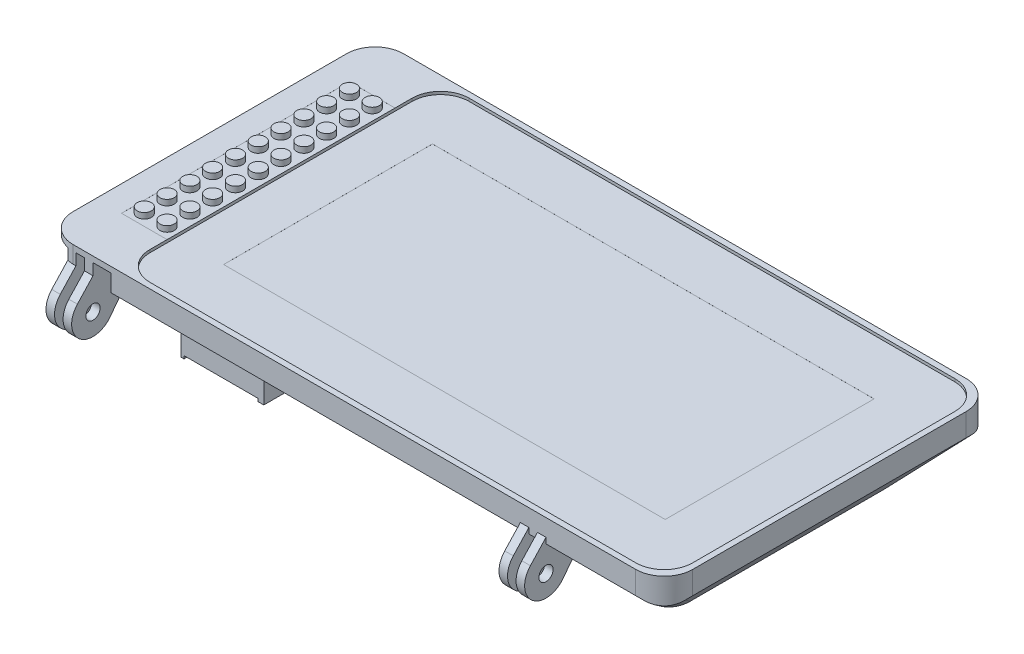
SolidWorks part; units mm, degrees
material "ABS"
ref_plane "Alzado" through (0, 0, 0) normal (0, 0, 1) x (1, 0, 0)
ref_plane "Planta" through (0, 0, 0) normal (0, 1, 0) x (1, 0, 0)
ref_plane "Vista lateral" through (0, 0, 0) normal (1, 0, 0) x (0, 0, -1)
sketch "Croquis1" plane through (0, 0, 0) normal (0, 1, 0) x (1, 0, 0)
  line L0 (-55, 0) -> (55, 0) construction
  line L1 (-108.75, -58) -> (108.75, -58)
  line L2 (-108.75, -58) -> (-108.75, 58)
  line L3 (-108.75, 58) -> (108.75, 58)
  line L4 (108.75, -58) -> (108.75, 58)
  line L5 (-108.75, -58) -> (108.75, 58) construction
  line L6 (-108.75, 58) -> (108.75, -58) construction
  line L7 (-83.75, -56) -> (106.75, -56)
  line L8 (-83.75, -56) -> (-83.75, 56)
  line L9 (-83.75, 56) -> (106.75, 56)
  line L10 (106.75, -56) -> (106.75, 56)
  line L11 (-83.75, -56) -> (106.75, 56) construction
  line L12 (-83.75, 56) -> (106.75, -56) construction
  line L13 (-91.75, 40) -> (-91.75, -40) construction
  line L14 (-99.75, -40) -> (-83.75, -40)
  line L15 (-99.75, -40) -> (-99.75, 40)
  line L16 (-99.75, 40) -> (-83.75, 40)
  line L17 (-83.75, -40) -> (-83.75, 40)
  line L18 (-99.75, -40) -> (-83.75, 40) construction
  line L19 (-99.75, 40) -> (-83.75, -40) construction
  line L20 (-67.25, -36.6556) -> (87.75, -36.6556)
  line L21 (-67.25, -36.6556) -> (-67.25, 36.6556)
  line L22 (-67.25, 36.6556) -> (87.75, 36.6556)
  line L23 (87.75, -36.6556) -> (87.75, 36.6556)
  line L24 (-67.25, -36.6556) -> (87.75, 36.6556) construction
  line L25 (-67.25, 36.6556) -> (87.75, -36.6556) construction
  circle A0 centre (-95.75, 36) radius 2.5
  circle A1 centre (-87.75, 36) radius 2.5
  circle A2 centre (-95.75, 28) radius 2.5
  circle A3 centre (-87.75, 28) radius 2.5
  circle A4 centre (-95.75, 20) radius 2.5
  circle A5 centre (-87.75, 20) radius 2.5
  circle A6 centre (-95.75, 12) radius 2.5
  circle A7 centre (-87.75, 12) radius 2.5
  circle A8 centre (-95.75, 4) radius 2.5
  circle A9 centre (-87.75, 4) radius 2.5
  circle A10 centre (-95.75, -4) radius 2.5
  circle A11 centre (-87.75, -4) radius 2.5
  circle A12 centre (-95.75, -12) radius 2.5
  circle A13 centre (-87.75, -12) radius 2.5
  circle A14 centre (-95.75, -20) radius 2.5
  circle A15 centre (-87.75, -20) radius 2.5
  circle A16 centre (-95.75, -28) radius 2.5
  circle A17 centre (-87.75, -28) radius 2.5
  circle A18 centre (-95.75, -36) radius 2.5
  circle A19 centre (-87.75, -36) radius 2.5
  point P0 (0, 0)
  point P6 (11.5, 0)
  point P13 (-91.75, 0)
  point P18 (10.25, 0)
  dimension "D9" = 5
  dimension "D10" = 4
  dimension "D12" = 4
  dimension "D1" = 116
  dimension "D2" = 217.5
  dimension "D3" = 2
  dimension "D4" = 2
  dimension "D5" = 25
  dimension "D6" = 16
  dimension "D7" = 19
  dimension "D8" = 155
  dimension "D11" = 8
  dimension "D14" = 80
  dimension "D13" = 10
sketch "Croquis2" plane through (0, 0, 0) normal (0, 1, 0) x (1, 0, 0)
  line L1 (-108.75, -58) -> (108.75, -58)
  line L2 (-108.75, -58) -> (-108.75, 58)
  line L3 (-108.75, 58) -> (108.75, 58)
  line L4 (108.75, -58) -> (108.75, 58)
  line L5 (-108.75, -58) -> (108.75, 58) construction
  line L6 (-108.75, 58) -> (108.75, -58) construction
  point P0 (0, 0)
extrude "Saliente-Extruir1" add sketch "Croquis2" along normal mid plane 24
sketch "Croquis3" plane through (0, 12, 0) normal (0, 1, 0) x (1, 0, 0)
  line L6 (-73.75, 56) -> (96.75, 56)
  line L8 (-83.75, 46) -> (-83.75, -46)
  line L9 (-73.75, -56) -> (96.75, -56)
  line L10 (106.75, 46) -> (106.75, -46)
  arc A0 (96.75, 56) -> (106.75, 46) centre (96.75, 46) cw
  arc A1 (96.75, -56) -> (106.75, -46) centre (96.75, -46) ccw
  arc A2 (-83.75, -46) -> (-73.75, -56) centre (-73.75, -46) ccw
  arc A3 (-83.75, 46) -> (-73.75, 56) centre (-73.75, 46) cw
  point P9 (106.75, -56)
  point P16 (-83.75, 56)
  dimension "D1" = 10
extrude "Cortar-Extruir1" cut sketch "Croquis3" against normal blind 1
sketch "Croquis4" plane through (0, 12, 0) normal (0, 1, 0) x (1, 0, 0)
  line L1 (-99.75, 40) -> (-83.75, 40)
  line L2 (-99.75, 40) -> (-99.75, -40)
  line L3 (-99.75, -40) -> (-83.75, -40)
  line L4 (-83.75, 40) -> (-83.75, -40)
extrude "Cortar-Extruir2" cut sketch "Croquis4" against normal blind 0.01
sketch "Croquis5" plane through (0, 11.99, 0) normal (0, 1, 0) x (1, 0, 0)
  circle A0 centre (-95.75, 36) radius 2.5
  circle A1 centre (-87.75, 36) radius 2.5
  circle A2 centre (-87.75, 28) radius 2.5
  circle A3 centre (-95.75, 28) radius 2.5
  circle A4 centre (-87.75, 20) radius 2.5
  circle A5 centre (-95.75, 20) radius 2.5
  circle A6 centre (-87.75, 12) radius 2.5
  circle A7 centre (-95.75, 12) radius 2.5
  circle A8 centre (-87.75, 4) radius 2.5
  circle A9 centre (-95.75, 4) radius 2.5
  circle A10 centre (-87.75, -4) radius 2.5
  circle A11 centre (-95.75, -4) radius 2.5
  circle A12 centre (-87.75, -12) radius 2.5
  circle A13 centre (-95.75, -12) radius 2.5
  circle A14 centre (-87.75, -20) radius 2.5
  circle A15 centre (-95.75, -20) radius 2.5
  circle A16 centre (-87.75, -28) radius 2.5
  circle A17 centre (-95.75, -28) radius 2.5
  circle A18 centre (-87.75, -36) radius 2.5
  circle A19 centre (-95.75, -36) radius 2.5
  dimension "D1" = 10
extrude "Saliente-Extruir2" add sketch "Croquis5" along normal blind 2
sketch "Croquis6" plane through (0, 11, 0) normal (0, 1, 0) x (1, 0, 0)
  line L1 (-67.25, 36.6556) -> (87.75, 36.6556)
  line L2 (-67.25, 36.6556) -> (-67.25, -36.6556)
  line L3 (-67.25, -36.6556) -> (87.75, -36.6556)
  line L4 (87.75, 36.6556) -> (87.75, -36.6556)
extrude "Cortar-Extruir3" cut sketch "Croquis6" against normal blind 0.01
sketch "Croquis7" plane through (0, -12, 0) normal (0, -1, 0) x (1, 0, 0)
  line L0 (94, 58) -> (94, -58) construction
  line L1 (94, 41.5) -> (-94, 41.5)
  line L2 (94, 41.5) -> (94, -41.5)
  line L3 (94, -41.5) -> (-94, -41.5)
  line L4 (-94, 41.5) -> (-94, -41.5)
  line L5 (94, 41.5) -> (-94, -41.5) construction
  line L6 (94, -41.5) -> (-94, 41.5) construction
  line L7 (-108.75, 58) -> (108.75, 58) construction
  line L8 (108.75, -58) -> (-108.75, -58) construction
  point P0 (0, 0)
  dimension "D1" = 83
  dimension "D2" = 188
ref_plane "Plano1" through (0, 4, 0) normal (0, 1, 0) x (1, 0, 0)
sketch "Croquis12" plane through (0, 4, 0) normal (0, 1, 0) x (1, 0, 0)
  line L1 (-108.75, 58) -> (108.75, 58)
  line L2 (-108.75, 58) -> (-108.75, -58)
  line L3 (-108.75, -58) -> (108.75, -58)
  line L4 (108.75, 58) -> (108.75, -58)
ref_plane "Plano2" through (-31.6273, 0, 28.2729) normal (-0.7455, 0, 0.6665) x (0.6665, 0, 0.7455)
sketch "Croquis13" plane through (-31.6273, 0, 28.2729) normal (-0.7455, 0, 0.6665) x (0.6665, 0, 0.7455)
  line L0 (-93.5874, -12) -> (-115.7192, 4)
  line L1 (-115.7192, 4) -> (-115.7192, -12)
  line L2 (-115.7192, -12) -> (-93.5874, -12)
sweep "Cortar-Barrer2" cut profiles "Croquis13" path "Croquis7"
sketch "Croquis14" plane through (0, 0, 0) normal (0, 0, 1) x (1, 0, 0)
  line L0 (-94, -12) -> (-108.75, -12)
  line L1 (-108.75, -12) -> (-108.75, 4)
  line L2 (-108.75, 4) -> (-94, -12)
  line L3 (94, -12) -> (108.75, 4)
  line L4 (108.75, 4) -> (108.75, -12)
  line L5 (108.75, -12) -> (94, -12)
extrude "Cortar-Extruir5" cut sketch "Croquis14" against normal through all both and the other way through all
sketch "Croquis15" plane through (0, -12, 0) normal (0, -1, 0) x (1, 0, 0)
  line L0 (-94, -41.5) -> (94, -41.5) construction
  line L1 (-16.5, -53.5) -> (-49, -53.5)
  line L2 (-16.5, -53.5) -> (-16.5, -37.5)
  line L3 (-16.5, -37.5) -> (-49, -37.5)
  line L4 (-49, -53.5) -> (-49, -37.5)
  line L5 (-94, 41.5) -> (-94, -41.5) construction
  dimension "D1" = 32.5
  dimension "D2" = 16
  dimension "D3" = 4
  dimension "D4" = 45
extrude "Cortar-Extruir6" cut sketch "Croquis15" against normal blind 10.5
sketch "Croquis16" plane through (0, -1.5, 0) normal (0, -1, 0) x (1, 0, 0)
  line L0 (-16.5, -52.3281) -> (-16.5, -41.5) construction
  line L1 (-49, -37.5) -> (-16.5, -37.5)
  line L2 (-49, -37.5) -> (-49, -53.5)
  line L3 (-49, -53.5) -> (-16.5, -53.5)
  line L4 (-16.5, -37.5) -> (-16.5, -53.5)
  dimension "D1" = 16
extrude "Saliente-Extruir4" add sketch "Croquis16" along normal blind 2 and the other way blind 2
sketch "Croquis17" plane through (0, -3.5, 0) normal (0, -1, 0) x (1, 0, 0)
  line L0 (-49, -52) -> (-50.5, -52)
  line L1 (-50.5, -52) -> (-50.5, -55.5)
  line L2 (-50.5, -55.5) -> (-15, -55.5)
  line L3 (-15, -55.5) -> (-15, -52)
  line L4 (-15, -52) -> (-16.5, -52)
  line L5 (-16.5, -52) -> (-16.5, -53.5)
  line L6 (-16.5, -53.5) -> (-49, -53.5)
  line L7 (-49, -50.2656) -> (-49, -53.5) construction
  line L8 (-49, -53.5) -> (-49, -52)
  dimension "D1" = 1.5
  dimension "D2" = 1.5
  dimension "D3" = 2
  dimension "D4" = 3.5
  dimension "D5" = 3.5
extrude "Saliente-Extruir10" add sketch "Croquis17" against normal blind 5 from offset 2 offset against normal yes
sketch "Croquis18" plane through (0, -12, 0) normal (0, -1, 0) x (1, 0, 0)
  line L0 (-16.5, -41.5) -> (94, -41.5) construction
  line L1 (-16.5, -41.5) -> (-16.5, -37.5) construction
  line L2 (-94, 0) -> (93.4097, 0) construction
  line L3 (-94, 41.5) -> (-94, -41.5) construction
  line L4 (14.5695, 0) -> (-14.5695, 0) construction
  circle A0 centre (-11.5, -37.5) radius 2.5
  circle A1 centre (63.5, -37.5) radius 2.5
  circle A2 centre (63.5, 37.5) radius 2.5
  circle A3 centre (-11.5, 37.5) radius 2.5
  dimension "D1" = 5
  dimension "D2" = 4
  dimension "D4" = 75
  dimension "D3" = 5
extrude "Cortar-Extruir7" cut sketch "Croquis18" against normal blind 9
sketch "Croquis19" plane through (0, -12, 0) normal (0, -1, 0) x (1, 0, 0)
  line L0 (-16.5, -41.5) -> (94, -41.5) construction
  line L1 (94, -41.5) -> (94, 41.5) construction
  line L2 (14.5695, 0) -> (-14.5695, 0) construction
  circle A0 centre (73.5, -35) radius 3.5
  circle A1 centre (73.5, 35) radius 3.5
  dimension "D1" = 7
  dimension "D2" = 6.5
  dimension "D3" = 20.5
extrude "Cortar-Extruir8" cut sketch "Croquis19" against normal blind 4
sketch "Croquis20" plane through (0, -8, 0) normal (0, -1, 0) x (1, 0, 0)
  circle A0 centre (73.5, 35) radius 1.5
  circle A1 centre (73.5, -35) radius 1.5
  dimension "D1" = 3
  dimension "D2" = 3
extrude "Cortar-Extruir9" cut sketch "Croquis20" against normal blind 4
sketch "Croquis21" plane through (0, -12, 0) normal (0, -1, 0) x (1, 0, 0)
  line L0 (-22.5, -34) -> (-22.5, -12.7)
  line L1 (-22.5, -12.7) -> (-10.5, -12.7)
  line L2 (-10.5, -12.7) -> (-10.5, 13.3)
  line L3 (-10.5, 13.3) -> (-22.5, 13.3)
  line L4 (-22.5, 13.3) -> (-22.5, 30.3)
  line L5 (-22.5, 30.3) -> (-18.5, 30.3)
  line L6 (-18.5, 30.3) -> (-18.5, 41.5)
  line L7 (94, 41.5) -> (-94, 41.5) construction
  line L8 (-22.5, -34) -> (-30.5, -34)
  line L9 (-30.5, -34) -> (-30.5, -31.5)
  line L10 (-30.5, -31.5) -> (-49.5, -31.5)
  line L11 (-49.5, -31.5) -> (-49.5, -35.5)
  line L13 (-56.5, -35.5) -> (-56.5, -31.5)
  line L14 (-56.5, -31.5) -> (-86, -31.5)
  line L15 (-86, -31.5) -> (-86, -34)
  line L16 (-86, -34) -> (-93, -34)
  line L17 (-93, -34) -> (-93, -31.5)
  line L18 (-93, -31.5) -> (-94, -31.5)
  line L19 (-94, 41.5) -> (-94, -41.5) construction
  line L20 (-16.5, -37.5) -> (-49, -37.5) construction
  line L21 (-16.5, -50.2656) -> (-16.5, -37.5) construction
  line L23 (-18.5, 41.5) -> (-18.5, 56.8)
  line L24 (-18.5, 56.8) -> (-40.5, 56.8)
  line L25 (-40.5, 56.8) -> (-40.5, 30.3)
  line L26 (-40.5, 30.3) -> (-37.5, 30.3)
  line L27 (-37.5, 30.3) -> (-37.5, 28.8)
  line L28 (-37.5, 28.8) -> (-45.5, 28.8)
  line L29 (-45.5, 28.8) -> (-45.5, 34.8)
  line L31 (-52.5, 34.8) -> (-52.5, 29.8)
  line L32 (-52.5, 29.8) -> (-62.5, 29.8)
  line L33 (-62.5, 29.8) -> (-62.5, 28.8)
  line L34 (-62.5, 28.8) -> (-71.5, 28.8)
  line L35 (-71.5, 28.8) -> (-71.5, 30.3)
  line L36 (-71.5, 30.3) -> (-68.5, 30.3)
  line L37 (-68.5, 30.3) -> (-68.5, 56.8)
  line L38 (-68.5, 56.8) -> (-85.5, 56.8)
  line L39 (-85.5, 56.8) -> (-85.5, 44.8)
  line L40 (-85.5, 44.8) -> (-83.5, 44.8)
  line L41 (-83.5, 44.8) -> (-83.5, 30.3)
  line L42 (-83.5, 30.3) -> (-79.5, 30.3)
  line L43 (-79.5, 30.3) -> (-79.5, 28.8)
  line L44 (-79.5, 28.8) -> (-108.75, 28.8)
  line L45 (-108.75, -58) -> (-108.75, 58) construction
  line L46 (-108.75, 28.8) -> (-108.75, -31.5)
  line L47 (-108.75, -31.5) -> (-94, -31.5)
  line L48 (-52.5, 34.8) -> (-45.5, 34.8) construction
  arc A0 (-56.5, -35.5) -> (-49.5, -35.5) centre (-53, -35.5) ccw
  arc A1 (-45.5, 34.8) -> (-52.5, 34.8) centre (-49, 34.8) ccw
  dimension "D12" = 3.5
  dimension "D22" = 3.5
  dimension "D1" = 3.5
  dimension "D2" = 26
  dimension "D3" = 12
  dimension "D4" = 21.3
  dimension "D5" = 6
  dimension "D6" = 17
  dimension "D7" = 4
  dimension "D8" = 8
  dimension "D9" = 19
  dimension "D10" = 6
  dimension "D11" = 7
  dimension "D13" = 4
  dimension "D14" = 7
  dimension "D15" = 1
  dimension "D16" = 26.5
  dimension "D17" = 22
  dimension "D18" = 3
  dimension "D19" = 1.5
  dimension "D20" = 8
  dimension "D21" = 7
  dimension "D23" = 6
  dimension "D24" = 1
  dimension "D25" = 9
  dimension "D26" = 10
  dimension "D27" = 1.5
  dimension "D28" = 3
  dimension "D29" = 17
  dimension "D30" = 12
  dimension "D32" = 2
  dimension "D33" = 8
  dimension "D34" = 1.5
extrude "Cortar-Extruir10" cut sketch "Croquis21" against normal blind 13.5
sketch "Croquis22" plane through (0, 1.5, 0) normal (0, -1, 0) x (1, 0, 0)
  line L0 (-37.5, 28.8) -> (-45.5, 28.8) construction
  line L1 (-22.5, 30.3) -> (-27.5, 30.3)
  line L2 (-22.5, 30.3) -> (-22.5, 28.8)
  line L3 (-22.5, 28.8) -> (-27.5, 28.8)
  line L4 (-27.5, 30.3) -> (-27.5, 28.8)
  dimension "D1" = 1.5
  dimension "D2" = 5
extrude "Saliente-Extruir11" add sketch "Croquis22" along normal blind 11
sketch "Croquis23" plane through (0, -12, 0) normal (0, -1, 0) x (1, 0, 0)
  line L0 (-68.5, 30.3) -> (-68.5, 41.5) construction
  line L2 (-42.5, 50.3) -> (-42.5, 31.3059)
  line L3 (-41.5059, 30.3059) -> (-40.5, 30.3)
  line L4 (-40.5, 30.3) -> (-37.5, 30.3)
  line L5 (-37.5, 30.3) -> (-37.5, 28.8)
  line L6 (-37.5, 28.8) -> (-45.5, 28.8)
  line L7 (-45.5, 28.8) -> (-45.5, 34.8)
  line L8 (-42.5, 50.3) -> (-66.5, 50.3)
  line L9 (-66.5, 50.3) -> (-66.5, 31.3)
  line L10 (-67.5, 30.3) -> (-71.5, 30.3)
  line L11 (-71.5, 30.3) -> (-71.5, 28.8)
  line L12 (-71.5, 28.8) -> (-45.5, 28.8)
  line L13 (-40.5, 41.5) -> (-40.5, 30.3) construction
  arc A0 (-42.5, 31.3059) -> (-41.5059, 30.3059) centre (-41.5, 31.3059) ccw
  arc A1 (-66.5, 31.3) -> (-67.5, 30.3) centre (-67.5, 31.3) cw
  line M2 (-68.5, 30.3) -> (-71.5, 30.3)
  line M3 (-71.5, 30.3) -> (-71.5, 28.8)
  line M4 (-71.5, 28.8) -> (-62.5, 28.8)
  line M5 (-62.5, 28.8) -> (-62.5, 29.8)
  line M6 (-62.5, 29.8) -> (-52.5, 29.8)
  line M7 (-52.5, 29.8) -> (-52.5, 34.8)
  arc M8 (-52.5, 34.8) -> (-45.5, 34.8) centre (-49, 34.8) cw
  line M9 (-45.5, 34.8) -> (-45.5, 28.8)
  line M10 (-45.5, 28.8) -> (-37.5, 28.8)
  line M11 (-37.5, 28.8) -> (-37.5, 30.3)
  line M12 (-37.5, 30.3) -> (-40.5, 30.3)
  line M14 (-40.5, 41.5) -> (-68.5, 41.5)
  dimension "D1" = 1
  dimension "D2" = 21.5
  dimension "D3" = 2
  dimension "D4" = 2
sketch "Croquis24" plane through (0, 1.5, 0) normal (0, -1, 0) x (1, 0, 0)
  line L0 (-52.5, 29.8) -> (-45.5, 29.8)
  line L1 (-45.5, 28.8) -> (-45.5, 34.8) construction
  line L2 (-45.5, 29.8) -> (-45.5, 34.8)
  line L3 (-52.5, 34.8) -> (-52.5, 29.8)
  arc A0 (-45.5, 34.8) -> (-52.5, 34.8) centre (-49, 34.8) ccw
extrude "Saliente-Extruir12" add sketch "Croquis24" along normal blind 6
extrude "Cortar-Extruir12" cut sketch "Croquis23" against normal blind 1 contours L8 L9 L2 M14 | L9 A1 L10 L3 A0 L2 M2 M3 M4 M5 M6 M7 M8 M9 M10 M11 M12 M14
sketch "Croquis25" plane through (0, -11, 0) normal (0, -1, 0) x (1, 0, 0)
  line L0 (-42.5, 41.5) -> (-42.5, 31.3059) construction
  line L1 (-42.5, 38.8) -> (-71.5, 38.8)
  line L2 (-42.5, 38.8) -> (-42.5, 47.3)
  line L3 (-42.5, 47.3) -> (-71.5, 47.3)
  line L4 (-71.5, 38.8) -> (-71.5, 47.3)
  line L5 (-62.5, 29.8) -> (-52.5, 29.8) construction
  dimension "D1" = 9
  dimension "D2" = 8.5
extrude "Cortar-Extruir13" cut sketch "Croquis25" against normal blind 11
sketch "Croquis26" plane through (0, 0, 0) normal (0, -1, 0) x (1, 0, 0)
  line L1 (-69.5, 47.3) -> (-42.5, 47.3)
  line L2 (-69.5, 47.3) -> (-69.5, 49.3)
  line L3 (-69.5, 49.3) -> (-42.5, 49.3)
  line L4 (-42.5, 47.3) -> (-42.5, 49.3)
  dimension "D1" = 2
extrude "Saliente-Extruir13" add sketch "Croquis26" along normal blind 11
sketch "Croquis27" plane through (0, -12, 0) normal (0, -1, 0) x (1, 0, 0)
  line L1 (-69.5, 49.3) -> (-68.5, 49.3)
  line L2 (-69.5, 49.3) -> (-69.5, 31.3)
  line L3 (-70.5, 30.3) -> (-68.5, 30.3)
  line L4 (-68.5, 49.3) -> (-68.5, 30.3)
  line L5 (-42.5, 49.3) -> (-40.5, 49.3)
  line L6 (-42.5, 49.3) -> (-42.5, 31.3)
  line L7 (-41.5, 30.3) -> (-40.5, 30.3)
  line L8 (-40.5, 49.3) -> (-40.5, 30.3)
  arc A0 (-42.5, 31.3) -> (-41.5, 30.3) centre (-41.5, 31.3) ccw
  arc A1 (-69.5, 31.3) -> (-70.5, 30.3) centre (-70.5, 31.3) cw
  dimension "D1" = 1
extrude "Saliente-Extruir14" add sketch "Croquis27" against normal blind 14
sketch "Croquis28" plane through (0, 4, 0) normal (0, 1, 0) x (1, 0, 0)
  line L0 (-108.75, 58) -> (-85.75, 58)
  line L1 (-108.75, 58) -> (108.75, 58) construction
  line L2 (-85.75, 58) -> (-85.75, 43)
  line L3 (-85.75, 43) -> (-102.75, 43)
  line L4 (-102.75, 43) -> (-102.75, 33)
  line L5 (-102.75, 33) -> (-108.75, 33)
  line L6 (-108.75, 58) -> (-108.75, -58) construction
  line L7 (-108.75, 33) -> (-108.75, 58)
  dimension "D1" = 25
  dimension "D2" = 6
  dimension "D3" = 10
  dimension "D4" = 23
extrude "Cortar-Extruir14" cut sketch "Croquis28" against normal blind 23
sketch "Croquis29" plane through (0, 4, 0) normal (0, 1, 0) x (1, 0, 0)
  line L0 (-108.75, -29.5) -> (-102.75, -29.5)
  line L1 (-108.75, 33) -> (-108.75, -58) construction
  line L2 (-102.75, -29.5) -> (-102.75, -44.8)
  line L3 (-102.75, -44.8) -> (-85.5, -44.8)
  line L4 (-85.5, -44.8) -> (-85.5, -58)
  line L5 (108.75, -58) -> (-108.75, -58) construction
  line L6 (-85.5, -58) -> (-108.75, -58)
  line L7 (-108.75, -58) -> (-108.75, -29.5)
  dimension "D1" = 28.5
  dimension "D2" = 6
extrude "Cortar-Extruir15" cut sketch "Croquis29" against normal blind 23 and the other way blind 6
sketch "Croquis30" plane through (0, -12, 0) normal (0, -1, 0) x (1, 0, 0)
  line L0 (108.75, 58) -> (-85.5, 58) construction
  line L1 (22.5, 26.5) -> (48.5, 26.5)
  line L2 (22.5, 26.5) -> (22.5, 58)
  line L3 (22.5, 58) -> (48.5, 58)
  line L4 (48.5, 26.5) -> (48.5, 58)
  line L5 (-18.5, 41.5) -> (-18.5, 55.4219) construction
  line L6 (94, 41.5) -> (-18.5, 41.5) construction
  dimension "D1" = 26
  dimension "D2" = 41
  dimension "D3" = 15
extrude "Cortar-Extruir16" cut sketch "Croquis30" against normal blind 16
sketch "Croquis31" plane through (0, 4, 0) normal (0, -1, 0) x (1, 0, 0)
  line L0 (-94, -31.5) -> (-107.75, -31.5)
  line L1 (-106.4453, -31.5) -> (-93, -31.5) construction
  line L2 (-107.75, -31.5) -> (-107.75, 28.8)
  line L3 (-79.5, 28.8) -> (-106.4453, 28.8) construction
  line L4 (-107.75, 28.8) -> (-94, 28.8)
  line L5 (-94, 28.8) -> (-94, 30.3)
  line L6 (-94, 30.3) -> (-108.75, 30.3)
  line L7 (-108.75, 29.5) -> (-108.75, 58) construction
  line L8 (-108.75, 30.3) -> (-108.75, -33)
  line L9 (-108.75, -33) -> (-94, -33)
  line L10 (-94, -31.5) -> (-94, -41.5) construction
  line L11 (-94, -33) -> (-94, -31.5)
  dimension "D1" = 1.5
  dimension "D2" = 1
extrude "Saliente-Extruir15" add sketch "Croquis31" along normal blind 12 and the other way blind 6
fillet "Redondeo1" radius 4 4 edges at (-108.75, 1, 30.3) (-108.75, -2, -33) (-107.75, -2.5424, -31.5) (-107.75, -2.5424, 28.8)
sketch "Croquis32" plane through (0, 0, 44.8) normal (0, 0, 1) x (1, 0, 0)
  line L0 (-102.75, 5) -> (-96.95, -8.8)
  line L1 (-102.75, 10) -> (-102.75, -2.5085) construction
  line L2 (-96.95, -8.8) -> (-102.75, -2.5085)
  line L3 (-102.75, -2.5085) -> (-102.75, 5)
  line L4 (-85.5, 10) -> (-102.75, 10) construction
  dimension "D1" = 5
extrude "Cortar-Extruir17" cut sketch "Croquis32" against normal up to surface (14.5 mm away) up to face at (-102.5375, 0.2983, 30.3)
ref_plane "Plano3" through (-100.75, 0, 0) normal (-1, 0, 0) x (0, 0, 1)
sketch "Croquis33" plane through (-100.75, 0, 0) normal (-1, 0, 0) x (0, 0, 1)
  line L0 (58, 10) -> (58, 6)
  line L1 (58, 10) -> (44.8, 10)
  line L2 (44.8, 10) -> (44.8, 0)
  line L3 (44.8, -8.8) -> (44.8, 5) construction
  line L4 (44.8, 0) -> (52.0227, -9.5301)
  line L5 (58, 6) -> (63.4864, 0.1136)
  line L7 (58, 10) -> (58, -5) construction
  arc A0 (52.0227, -9.5301) -> (63.4864, 0.1136) centre (58, -5) ccw
  circle A1 centre (58, -5) radius 2.5
  dimension "D3" = 15
  dimension "D5" = 5
  dimension "D1" = 10
  dimension "D2" = 15
  dimension "D4" = 6
extrude "Saliente-Extruir16" add sketch "Croquis33" against normal blind 3
pattern_linear "MatrizL1" count 2 spacing 6 along (1, 0, 0) of "Saliente-Extruir16"
sketch "Croquis34" plane through (48.5, 0, 0) normal (-1, 0, 0) x (0, 0, 1)
  line L0 (58, 4) -> (41.5, -12)
  line L1 (41.5, -12) -> (58, 4) construction
  line L2 (41.5, -12) -> (40.0635, -12)
  line L3 (40.0635, -12) -> (55.9817, 3.4358)
  line L4 (26.5, 4) -> (58, 4) construction
  line L5 (57.374, 4) -> (58, 4)
  arc A0 (55.9817, 3.4358) -> (57.374, 4) centre (57.374, 2) cw
  point P11 (56.5635, 4)
  dimension "D2" = 2
  dimension "D1" = 1
extrude "Cortar-Extruir18" cut sketch "Croquis34" against normal blind 21
pattern_linear "MatrizL2" count 2 spacing 159 along (1, 0, 0) of "MatrizL1", "Saliente-Extruir16"
fillet "Redondeo2" radius 10 4 edges at (108.75, 8, 58) (108.75, 8, -58) (-108.75, 11, 58) (-108.75, 8, -58)
fillet "Redondeo3" radius 10 4 edges at (-95.475, -10.4, 43.15) (-99.0455, -6.527, -43) (99.9916, -5.5006, 48.2025) (99.9916, -5.5006, -48.2025)
